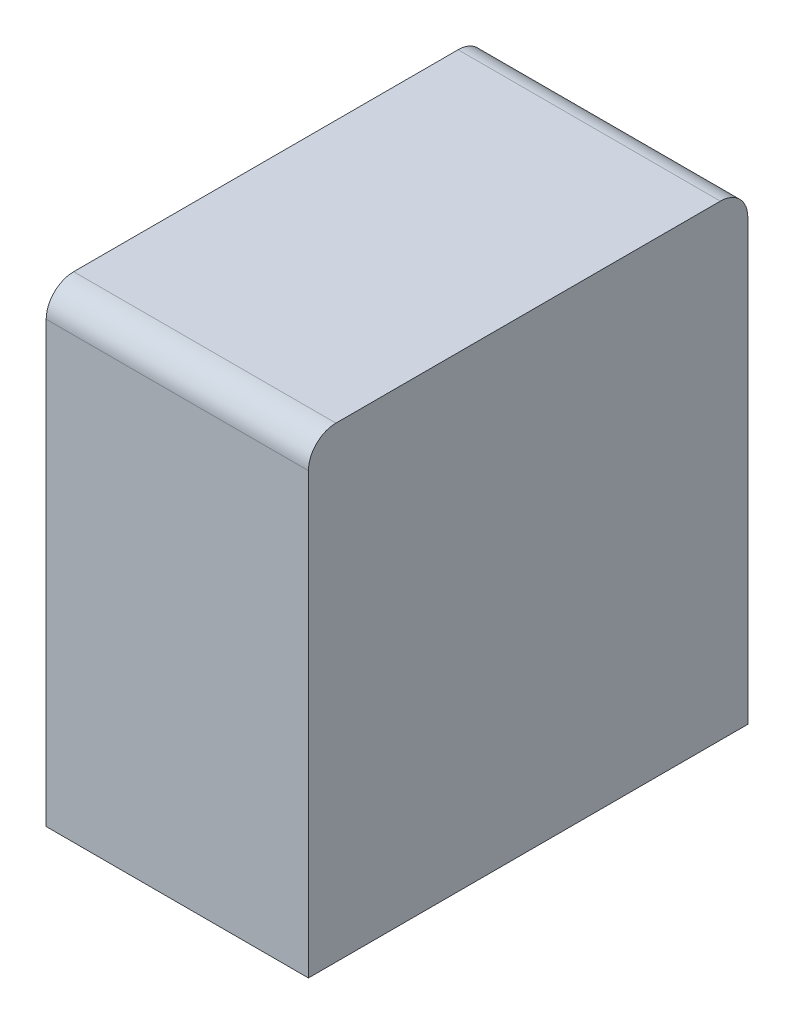
SolidWorks part; units mm, degrees
ref_plane "前视基准面" through (0, 0, 0) normal (0, 0, 1) x (1, 0, 0)
ref_plane "上视基准面" through (0, 0, 0) normal (0, 1, 0) x (1, 0, 0)
ref_plane "右视基准面" through (0, 0, 0) normal (1, 0, 0) x (0, 0, -1)
sketch "草图1" plane through (0, 0, 0) normal (0, 1, 0) x (1, 0, 0)
  line L0 (0, 14.1902) -> (0, -10.6155) construction
  line L1 (-22.4154, 0) -> (19.6333, 0) construction
  line L3 (-4.775, 8) -> (4.775, 8)
  line L4 (-4.775, 8) -> (-4.775, -8)
  line L5 (-4.775, -8) -> (4.775, -8)
  line L6 (4.775, 8) -> (4.775, -8)
  dimension "D1" = 9.55
  dimension "D2" = 16
extrude "拉伸1" add sketch "草图1" along normal blind 17
sketch "草图2" plane through (0, 0, 0) normal (0, -1, 0) x (1, 0, 0)
  line L0 (1.2418, 0) -> (-2.2702, 0) construction
  circle A0 centre (-2, 0) radius 0.6
  dimension "D1" = 1.2
  dimension "D2" = 2
extrude "拉伸2" add sketch "草图2" along normal blind 4
fillet "圆角1" radius 1 2 edges at (0, 17, 8) (0, 17, -8)
